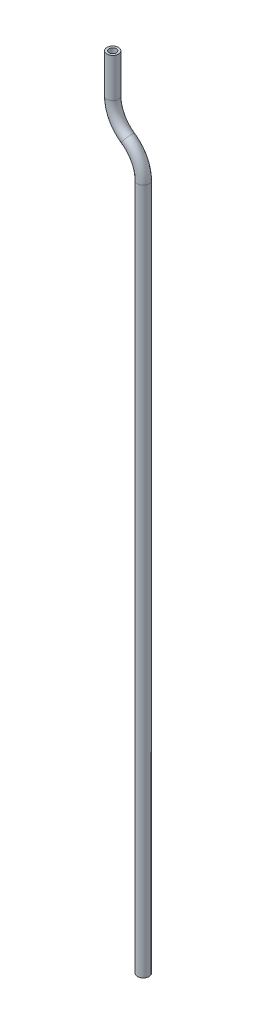
SolidWorks part; units mm, degrees
ref_plane "Front Plane" through (0, 0, 0) normal (0, 0, 1) x (1, 0, 0)
ref_plane "Top Plane" through (0, 0, 0) normal (0, 1, 0) x (1, 0, 0)
ref_plane "Right Plane" through (0, 0, 0) normal (1, 0, 0) x (0, 0, -1)
sketch "Illustrative smooth utility route" plane through (0, 0, 0) normal (0, 0, 1) x (1, 0, 0)
  line L0 (-13.55, 0) -> (-13.55, -13.5)
  line L1 (-3, -33.5) -> (-3, -270.5)
  arc A0 (-13.55, -13.5) -> (-8.275, -23.5) centre (-1.4338, -13.5) ccw
  arc A1 (-8.275, -23.5) -> (-3, -33.5) centre (-15.1162, -33.5) cw
sketch "Utility circular cross section" plane through (0, 0, 0) normal (0, 1, 0) x (1, 0, 0)
  circle A0 centre (-13.55, 0) radius 2
  circle A1 centre (-13.55, 0) radius 1.25
sweep "Native hollow utility sweep" add profiles "Utility circular cross section" path "Illustrative smooth utility route"
